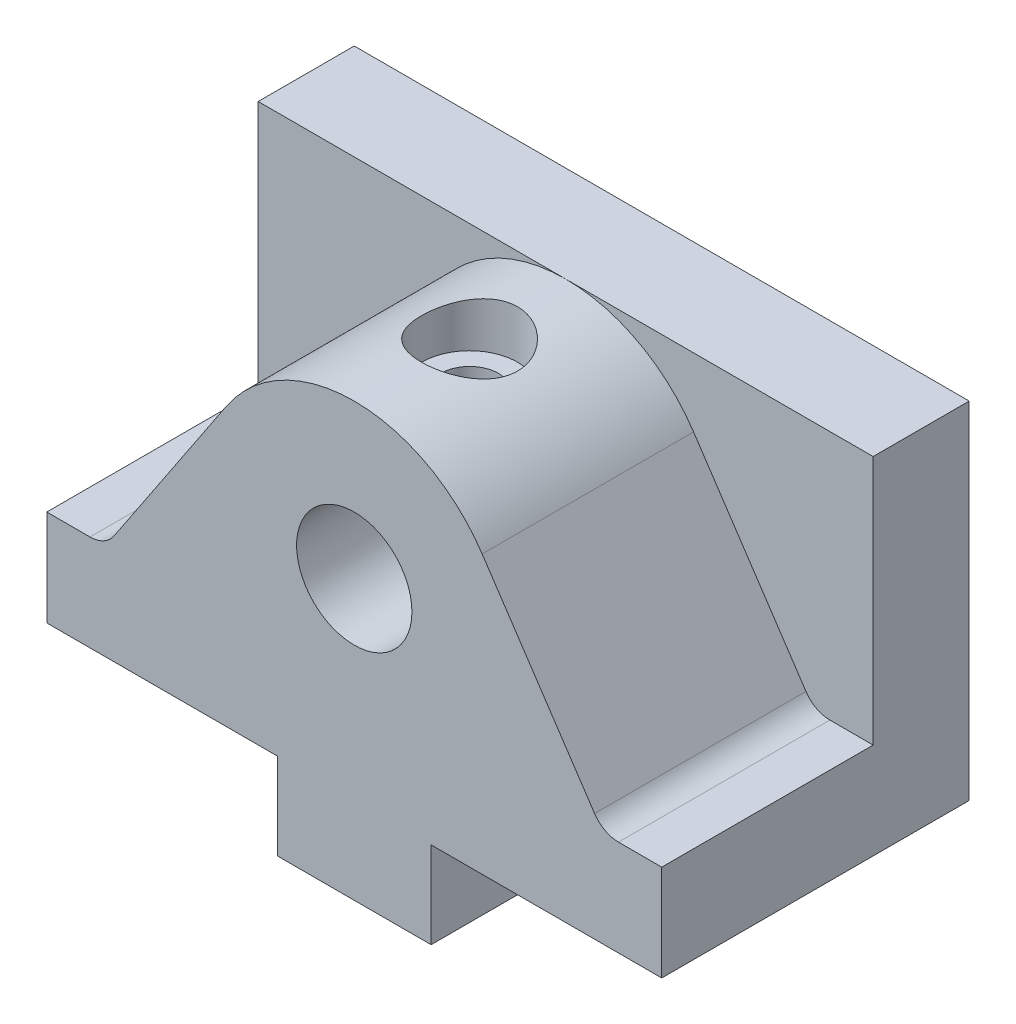
SolidWorks part; units mm, degrees
ref_plane "Front Plane" through (0, 0, 0) normal (0, 0, 1) x (1, 0, 0)
ref_plane "Top Plane" through (0, 0, 0) normal (0, 1, 0) x (1, 0, 0)
ref_plane "Right Plane" through (0, 0, 0) normal (1, 0, 0) x (0, 0, -1)
sketch "Sketch1" plane through (0, 0, 0) normal (0, 0, 1) x (1, 0, 0)
  line L1 (-32, 18) -> (32, 18)
  line L2 (-32, 18) -> (-32, -18)
  line L3 (-32, -18) -> (32, -18)
  line L4 (32, 18) -> (32, -18)
extrude "Boss-Extrude1" add sketch "Sketch1" along normal mid plane 32
sketch "Sketch2" plane through (0, 0, 16) normal (0, 0, 1) x (1, 0, 0)
  line L0 (32, 18) -> (-32, 18) construction
  line L1 (-32, -8) -> (-27.5, -8)
  line L2 (-32, 18) -> (-32, -18) construction
  line L3 (32, -18) -> (32, 18) construction
  line L4 (-32, -18) -> (32, -18) construction
  line L5 (-25.0037, -6.6639) -> (-13.3134, 10.8742)
  line L6 (13.3126, 10.8755) -> (25.0076, -6.6661)
  line L7 (-32, -8) -> (-48.3665, -8)
  line L8 (27.5, -8.002) -> (32, -8.0075)
  line L9 (-48.3665, -8) -> (-48.3665, 30.1546)
  line L10 (-48.3665, 30.1546) -> (36.6622, 30.1546)
  line L11 (36.6622, 30.1546) -> (36.6622, -8.0075)
  line L12 (36.6622, -8.0075) -> (32, -8.0075)
  arc A0 (13.3126, 10.8755) -> (-13.3134, 10.8742) centre (0, 2) ccw
  arc A1 (-25.0037, -6.6639) -> (-27.5, -8) centre (-27.5, -5) cw
  arc A2 (27.5, -8.002) -> (25.0076, -6.6661) centre (27.5037, -5.002) cw
  point P19 (25.8969, -8)
  dimension "D1" = 3
  dimension "D3" = 3
  dimension "D5" = 67.377
  dimension "D2" = 10
  dimension "D4" = 55
extrude "Cut-Extrude1" cut sketch "Sketch2" against normal blind 22
sketch "Sketch3" plane through (0, 0, 16) normal (0, 0, 1) x (1, 0, 0)
  circle A0 centre (0, 2) radius 6
  arc A1 (13.3126, 10.8755) -> (0, 18) centre (0, 2) ccw construction
  dimension "D1" = 12
extrude "Cut-Extrude2" cut sketch "Sketch3" against normal blind 24
sketch "Sketch4" plane through (0, 0, 16) normal (0, 0, 1) x (1, 0, 0)
  line L1 (-8, -18) -> (8, -18)
  line L2 (-8, -18) -> (-8, -27)
  line L3 (-8, -27) -> (8, -27)
  line L4 (8, -18) -> (8, -27)
  line L5 (-8, -18) -> (8, -27) construction
  line L6 (-8, -27) -> (8, -18) construction
  point P0 (0, -22.5)
  dimension "D1" = 16
  dimension "D2" = 9
extrude "Boss-Extrude3" add sketch "Sketch4" against normal blind 32
sketch "Sketch5" plane through (0, -27, 0) normal (0, -1, 0) x (-1, 0, 0)
  point P0 (0, -8)
  point P1 (0, 8)
hole_wizard "Ø6.0mm Dowel Hole1" positions "3DSketch1" profile "Sketch6" hole size "Ø6.0" standard "ISO"
sketch3d "3DSketch1"
  point P0 (0, -27, 8)
  point P3 (0, -27, -8)
sketch "Sketch6" plane through (0, -27, 8) normal (1, 0, 0) x (0, 0, -1)
  line L0 (0, 0) -> (0, 17.8026)
  line L1 (0, 17.8026) -> (3, 16)
  line L2 (3, 16) -> (3, 0)
  line L5 (3, 0) -> (0, 0)
  line L10 (0, 17.8026) -> (-3, 16) construction
  line L11 (0, -6.35) -> (0, 107.95) construction
  dimension "Hole Dia." = 6
  dimension "Hole Depth" = 16
  dimension "Drill Angle" = 118
sketch "Sketch7" plane through (0, 18, 0) normal (0, 1, 0) x (1, 0, 0)
  line L0 (-8, 16) -> (8, 16) construction
  point P0 (0, -4)
  point P1 (0, 16)
  dimension "D1" = 20
hole_wizard "CBORE for M6 Hex Head Bolt2" positions "Sketch11" profile "Sketch10" counterbore size "M6" standard "ISO"
sketch "Sketch11" plane through (0, 18, 0) normal (0, 1, 0) x (1, 0, 0)
  point P0 (0, -4)
sketch "Sketch10" plane through (0, 18, 4) normal (1, 0, 0) x (0, 0, 1)
  line L0 (0, 0) -> (0, 14.8026)
  line L1 (0, 14.8026) -> (3, 13)
  line L2 (3, 13) -> (3, 5)
  line L3 (3, 5) -> (5, 5)
  line L4 (5, 5) -> (5, 0)
  line L5 (5, 0) -> (0, 0)
  line L10 (0, 14.8026) -> (-3, 13) construction
  line L11 (0, -6.35) -> (0, 107.95) construction
  dimension "Hole Dia." = 6
  dimension "Hole Depth" = 13
  dimension "C'Bore Dia." = 10
  dimension "C'Bore Depth" = 5
  dimension "Drill Angle" = 118
